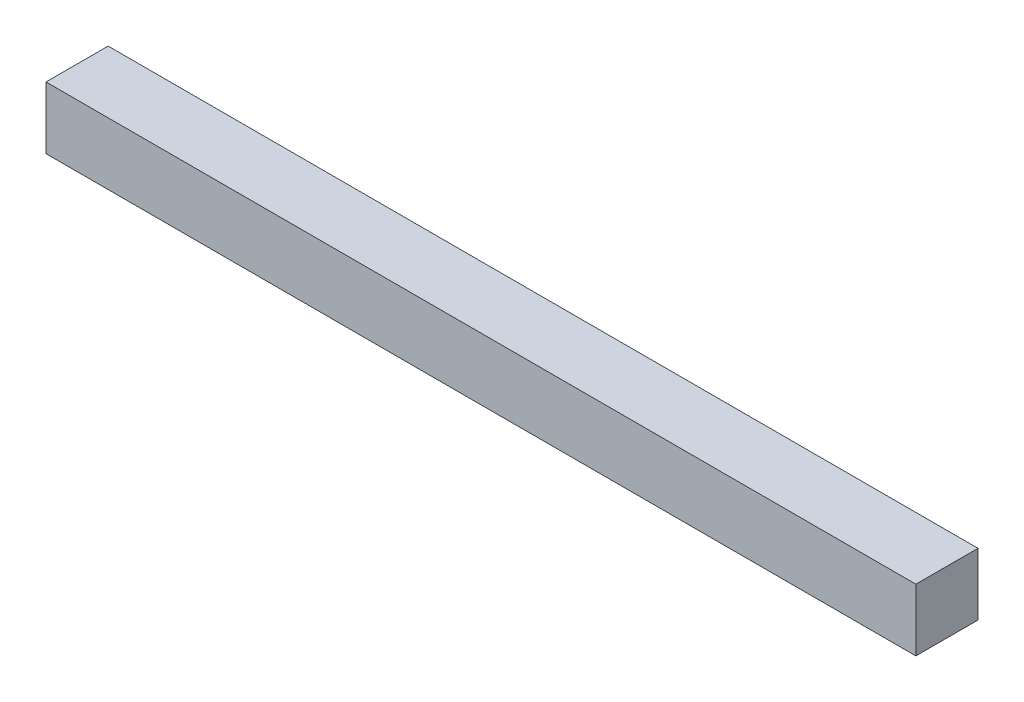
SolidWorks part; units mm, degrees
material "6061-T6 (SS)"
ref_plane "Front Plane" through (0, 0, 0) normal (0, 0, 1) x (1, 0, 0)
ref_plane "Top Plane" through (0, 0, 0) normal (0, 1, 0) x (1, 0, 0)
ref_plane "Right Plane" through (0, 0, 0) normal (1, 0, 0) x (0, 0, -1)
sketch "Sketch5" plane through (0, 0, 0) normal (0, 1, 0) x (1, 0, 0)
  line L1 (-266.7, 19.05) -> (266.7, 19.05)
  line L2 (-266.7, 19.05) -> (-266.7, -19.05)
  line L3 (-266.7, -19.05) -> (266.7, -19.05)
  line L4 (266.7, 19.05) -> (266.7, -19.05)
  point P4 (0, -19.05)
  point P5 (266.7, 0)
  dimension "D1" = 38.1
  dimension "D2" = 533.4
extrude "Boss-Extrude3" add sketch "Sketch5" along normal blind 38.1 separate body
